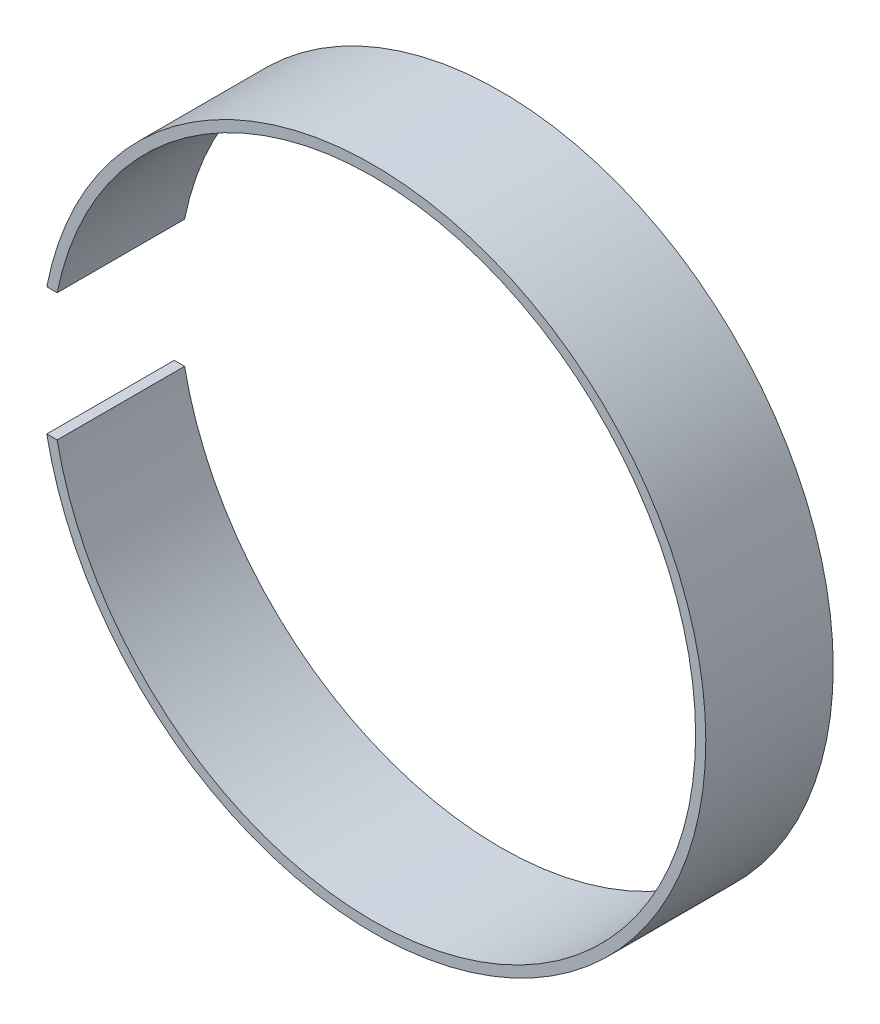
SolidWorks part; units mm, degrees
material "ABS"
ref_plane "Front Plane" through (0, 0, 0) normal (0, 0, 1) x (1, 0, 0)
ref_plane "Top Plane" through (0, 0, 0) normal (0, 1, 0) x (1, 0, 0)
ref_plane "Right Plane" through (0, 0, 0) normal (1, 0, 0) x (0, 0, -1)
sketch "Sketch1" plane through (0, 0, 0) normal (0, 0, 1) x (1, 0, 0)
  line L0 (0, 0) -> (-652.5, 0) construction
  line L1 (-640.4149, -125) -> (-620.0252, -125)
  line L2 (-640.4149, 125) -> (-620.0252, 125)
  arc A0 (-620.0252, -125) -> (-620.0252, 125) centre (0, 0) ccw
  arc A1 (-640.4149, -125) -> (-640.4149, 125) centre (0, 0) ccw
  circle A2 centre (0, 0) radius 652.5 construction
  circle A3 centre (0, 0) radius 632.5 construction
  arc A4 (-640.4149, 125) -> (-652.5, 0) centre (0, 0) ccw construction
  point P11 (0, 0)
  dimension "D1" = 1265
  dimension "D3" = 125
  dimension "D2" = 20
extrude "Boss-Extrude1" add sketch "Sketch1" along normal blind 250
